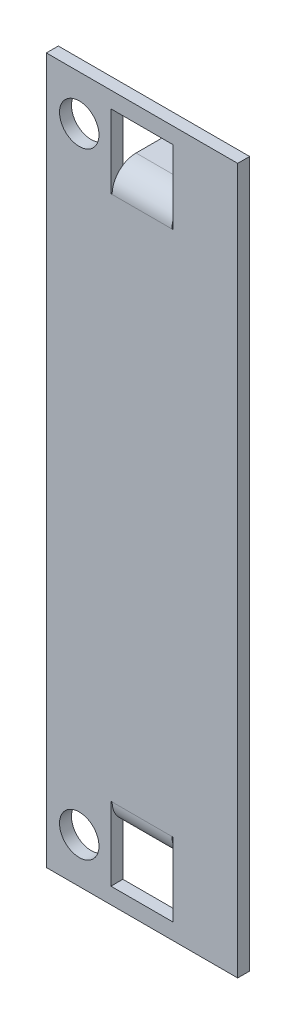
SolidWorks part; units mm, degrees
other "Ballast Retaining Bar"
ref_plane "Front Plane" through (0, 0, 0) normal (0, 0, 1) x (1, 0, 0)
ref_plane "Top Plane" through (0, 0, 0) normal (0, 1, 0) x (1, 0, 0)
ref_plane "Right Plane" through (0, 0, 0) normal (1, 0, 0) x (0, 0, -1)
sketch3d "Clamp Bar Sketch datum points"
  point P0 (0, 0, 140)
  point P1 (10, 0, 140)
  point P2 (0, 10, 140)
ref_plane "Clamp Bar Sketch plane" through (0, 0, 140) normal (0, 0, 1) x (1, 0, 0)
sketch "Clamp Bar Sketch" plane through (0, 0, 140) normal (0, 0, 1) x (1, 0, 0)
  line L0 (-23.5, -59) -> (8.5, -59)
  line L1 (8.5, -59) -> (8.5, 59)
  line L2 (8.5, 59) -> (-23.5, 59)
  line L3 (-23.5, 59) -> (-23.5, -59)
extrude "Clamp Bar" add sketch "Clamp Bar Sketch" along normal blind 2 separate body
sketch3d "Finger Relief Sketch datum points"
  point P0 (0, 0, 139.8)
  point P1 (10, 0, 139.8)
  point P2 (0, 10, 139.8)
ref_plane "Finger Relief Sketch plane" through (0, 0, 139.8) normal (0, 0, 1) x (1, 0, 0)
sketch "Finger Relief Sketch" plane through (0, 0, 139.8) normal (0, 0, 1) x (1, 0, 0)
  line L0 (-12.7, -56.3) -> (-2.3, -56.3)
  line L1 (-2.3, -56.3) -> (-2.3, -44)
  line L2 (-2.3, -44) -> (-12.7, -44)
  line L3 (-12.7, -44) -> (-12.7, -56.3)
  line L4 (-12.7, 44) -> (-2.3, 44)
  line L5 (-2.3, 44) -> (-2.3, 56.3)
  line L6 (-2.3, 56.3) -> (-12.7, 56.3)
  line L7 (-12.7, 56.3) -> (-12.7, 44)
extrude "Finger Reliefs" cut sketch "Finger Relief Sketch" along normal blind 2.4
sketch3d "Folded Finger Sketch datum points"
  point P0 (-12.5, 0, 0)
  point P1 (-12.5, 10, 0)
  point P2 (-12.5, 0, 10)
ref_plane "Folded Finger Sketch plane" through (-12.5, 0, 0) normal (1, 0, 0) x (0, 0, -1)
sketch "Folded Finger Sketch" plane through (-12.5, 0, 0) normal (1, 0, 0) x (0, 0, -1)
  line L0 (-138, -48) -> (-130, -48)
  line L1 (-130, -48) -> (-130, -46)
  line L2 (-130, -46) -> (-138, -46)
  line L3 (-140, -44) -> (-142, -44)
  line L4 (-138, 48) -> (-130, 48)
  line L5 (-130, 48) -> (-130, 46)
  line L6 (-130, 46) -> (-138, 46)
  line L7 (-140, 44) -> (-142, 44)
  arc A0 (-142, -44) -> (-138, -48) centre (-138, -44) ccw
  arc A1 (-140, -44) -> (-138, -46) centre (-138, -44) ccw
  arc A2 (-138, 48) -> (-142, 44) centre (-138, 44) ccw
  arc A3 (-138, 46) -> (-140, 44) centre (-138, 44) ccw
extrude "Folded Fingers" add sketch "Folded Finger Sketch" along normal blind 10
sketch3d "Stud Clearances Sketch datum points"
  point P0 (0, 0, 139.8)
  point P1 (10, 0, 139.8)
  point P2 (0, 10, 139.8)
ref_plane "Stud Clearances Sketch plane" through (0, 0, 139.8) normal (0, 0, 1) x (1, 0, 0)
sketch "Stud Clearances Sketch" plane through (0, 0, 139.8) normal (0, 0, 1) x (1, 0, 0)
  circle A0 centre (-18, -51.5) radius 3.3
  circle A1 centre (-18, 51.5) radius 3.3
extrude "Stud Clearances" cut sketch "Stud Clearances Sketch" along normal blind 2.4
